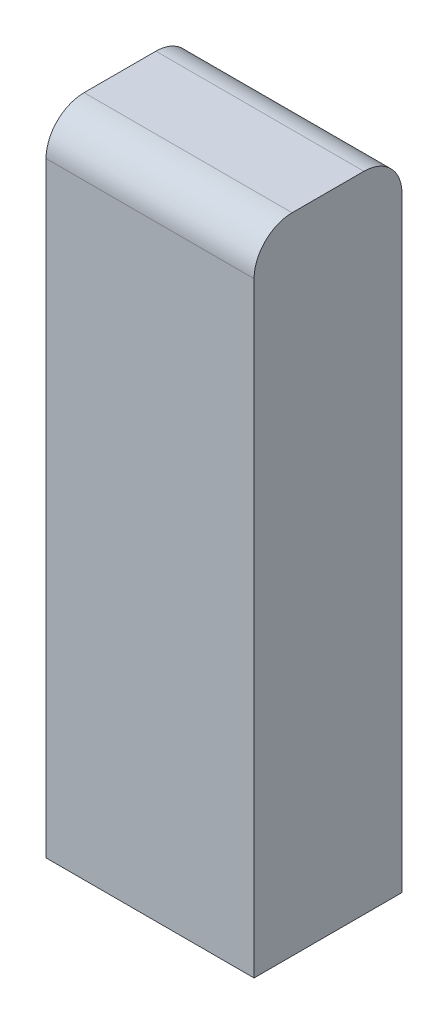
SolidWorks part; units mm, degrees
ref_plane "Front Plane" through (0, 0, 0) normal (0, 0, 1) x (1, 0, 0)
ref_plane "Top Plane" through (0, 0, 0) normal (0, 1, 0) x (1, 0, 0)
ref_plane "Right Plane" through (0, 0, 0) normal (1, 0, 0) x (0, 0, -1)
sketch "Sketch1" plane through (0, 0, 0) normal (0, 0, 1) x (1, 0, 0)
  line L1 (-17.3609, -53.721) -> (17.3609, -53.721)
  line L2 (-17.3609, -53.721) -> (-17.3609, 53.721)
  line L3 (-17.3609, 53.721) -> (17.3609, 53.721)
  line L4 (17.3609, -53.721) -> (17.3609, 53.721)
  line L5 (-17.3609, -53.721) -> (17.3609, 53.721) construction
  line L6 (-17.3609, 53.721) -> (17.3609, -53.721) construction
  point P0 (0, 0)
  dimension "D1" = 107.442
  dimension "D2" = 34.7218
extrude "Boss-Extrude1" add sketch "Sketch1" along normal blind 24.6888
fillet "Fillet2" radius 6.35 2 edges at (0, 53.721, 0) (0, 53.721, 24.6888)
